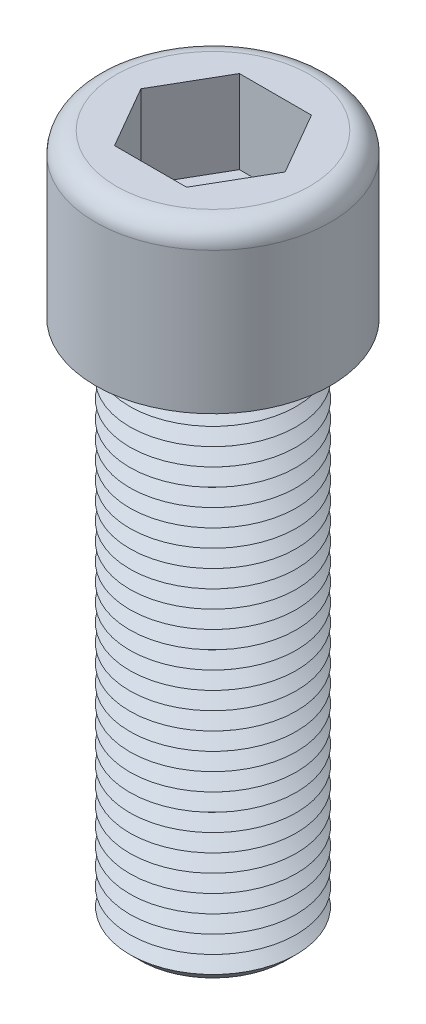
SolidWorks part; units mm, degrees
ref_plane "前视基准面" through (0, 0, 0) normal (0, 0, 1) x (1, 0, 0)
ref_plane "上视基准面" through (0, 0, 0) normal (0, 1, 0) x (1, 0, 0)
ref_plane "右视基准面" through (0, 0, 0) normal (1, 0, 0) x (0, 0, -1)
sketch "草图1" plane through (0, 0, 0) normal (0, 0, 1) x (1, 0, 0)
  line B0 (0, 0) -> (0, 32.8)
  line B1 (3.5, 0) -> (0, 0)
  line B2 (3.5, 0) -> (3.9917, 0.4917)
  line B3 (4, 25) -> (5.65, 25)
  line B4 (0, 32.8) -> (4.65, 32.8)
  line B5 (5.65, 25) -> (5.65, 31.8)
  line B6 (4, 25) -> (3.4, 24.5773)
  line B7 (4, 24.1547) -> (3.4, 24.5773)
  line B8 (4, 24.1547) -> (3.4, 23.732)
  line B9 (4, 23.3094) -> (3.4, 23.732)
  line B10 (4, 23.3094) -> (3.4, 22.8867)
  line B11 (4, 22.464) -> (3.4, 22.8867)
  line B12 (4, 22.464) -> (3.4, 22.0414)
  line B13 (4, 21.6187) -> (3.4, 22.0414)
  line B14 (4, 21.6187) -> (3.4, 21.1961)
  line B15 (4, 20.7734) -> (3.4, 21.1961)
  line B16 (4, 20.7734) -> (3.4, 20.3508)
  line B17 (4, 19.9281) -> (3.4, 20.3508)
  line B18 (4, 19.9281) -> (3.4, 19.5054)
  line B19 (4, 19.0828) -> (3.4, 19.5054)
  line B20 (4, 19.0828) -> (3.4, 18.6601)
  line B21 (4, 18.2375) -> (3.4, 18.6601)
  line B22 (4, 18.2375) -> (3.4, 17.8148)
  line B23 (4, 17.3921) -> (3.4, 17.8148)
  line B24 (4, 17.3921) -> (3.4, 16.9695)
  line B25 (4, 16.5468) -> (3.4, 16.9695)
  line B26 (4, 16.5468) -> (3.4, 16.1242)
  line B27 (4, 15.7015) -> (3.4, 16.1242)
  line B28 (4, 15.7015) -> (3.4, 15.2788)
  line B29 (4, 14.8562) -> (3.4, 15.2788)
  line B30 (4, 14.8562) -> (3.4, 14.4335)
  line B31 (4, 14.0109) -> (3.4, 14.4335)
  line B32 (4, 14.0109) -> (3.4, 13.5882)
  line B33 (4, 13.1656) -> (3.4, 13.5882)
  line B34 (4, 13.1656) -> (3.4, 12.7429)
  line B35 (4, 12.3202) -> (3.4, 12.7429)
  line B36 (4, 12.3202) -> (3.4, 11.8976)
  line B37 (4, 11.4749) -> (3.4, 11.8976)
  line B38 (4, 11.4749) -> (3.4, 11.0523)
  line B39 (4, 10.6296) -> (3.4, 11.0523)
  line B40 (4, 10.6296) -> (3.4, 10.2069)
  line B41 (4, 9.7843) -> (3.4, 10.2069)
  line B42 (4, 9.7843) -> (3.4, 9.3616)
  line B43 (4, 8.939) -> (3.4, 9.3616)
  line B44 (4, 8.939) -> (3.4, 8.5163)
  line B45 (4, 8.0936) -> (3.4, 8.5163)
  line B46 (4, 8.0936) -> (3.4, 7.671)
  line B47 (4, 7.2483) -> (3.4, 7.671)
  line B48 (4, 7.2483) -> (3.4, 6.8257)
  line B49 (4, 6.403) -> (3.4, 6.8257)
  line B50 (4, 6.403) -> (3.4, 5.9804)
  line B51 (4, 5.5577) -> (3.4, 5.9804)
  line B52 (4, 5.5577) -> (3.4, 5.135)
  line B53 (4, 4.7124) -> (3.4, 5.135)
  line B54 (4, 4.7124) -> (3.4, 4.2897)
  line B55 (4, 3.8671) -> (3.4, 4.2897)
  line B56 (4, 3.8671) -> (3.4, 3.4444)
  line B57 (4, 3.0217) -> (3.4, 3.4444)
  line B58 (4, 3.0217) -> (3.4, 2.5991)
  line B59 (4, 2.1764) -> (3.4, 2.5991)
  line B60 (4, 2.1764) -> (3.4, 1.7538)
  line B61 (4, 1.3311) -> (3.4, 1.7538)
  line B62 (4, 1.3311) -> (3.4, 0.9084)
  line B63 (3.9917, 0.4917) -> (3.4, 0.9084)
  arc B64 (5.65, 31.8) -> (4.65, 32.8) centre (4.65, 31.8) ccw
sketch_block_instance "A$C39A15E5E-1"
sketch_block "A$C39A15E5E"
revolve "旋转1" add sketch "草图1" angle 360 about L0
sketch "草图3" plane through (0, 32.8, 0) normal (0, 1, 0) x (1, 0, 0)
  line L1 (3.4641, 0) -> (1.7321, 3)
  line L2 (1.7321, 3) -> (-1.7321, 3)
  line L3 (-1.7321, 3) -> (-3.4641, 0)
  line L4 (-3.4641, 0) -> (-1.7321, -3)
  line L5 (-1.7321, -3) -> (1.7321, -3)
  line L6 (1.7321, -3) -> (3.4641, 0)
extrude "切除-拉伸1" cut sketch "草图3" against normal blind 4
